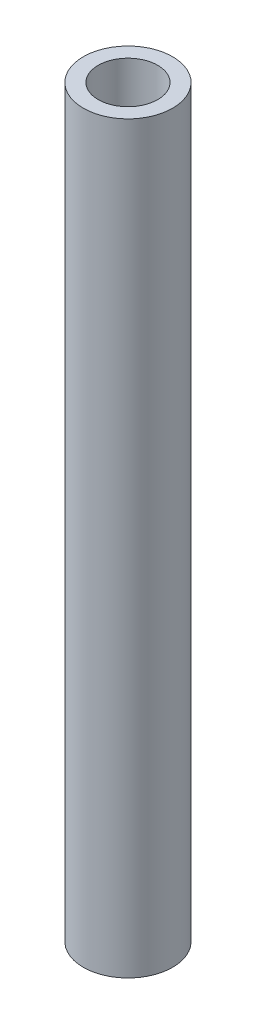
SolidWorks part; units mm, degrees
ref_plane "Front Plane" through (0, 0, 0) normal (0, 0, 1) x (1, 0, 0)
ref_plane "Top Plane" through (0, 0, 0) normal (0, 1, 0) x (1, 0, 0)
ref_plane "Right Plane" through (0, 0, 0) normal (1, 0, 0) x (0, 0, -1)
sketch "Sketch1" plane through (0, 0, 0) normal (0, 1, 0) x (1, 0, 0)
  circle A0 centre (0, 0) radius 20
  circle A1 centre (0, 0) radius 30
  dimension "D1" = 40
  dimension "D2" = 60
extrude "Boss-Extrude1" add sketch "Sketch1" along normal blind 500
